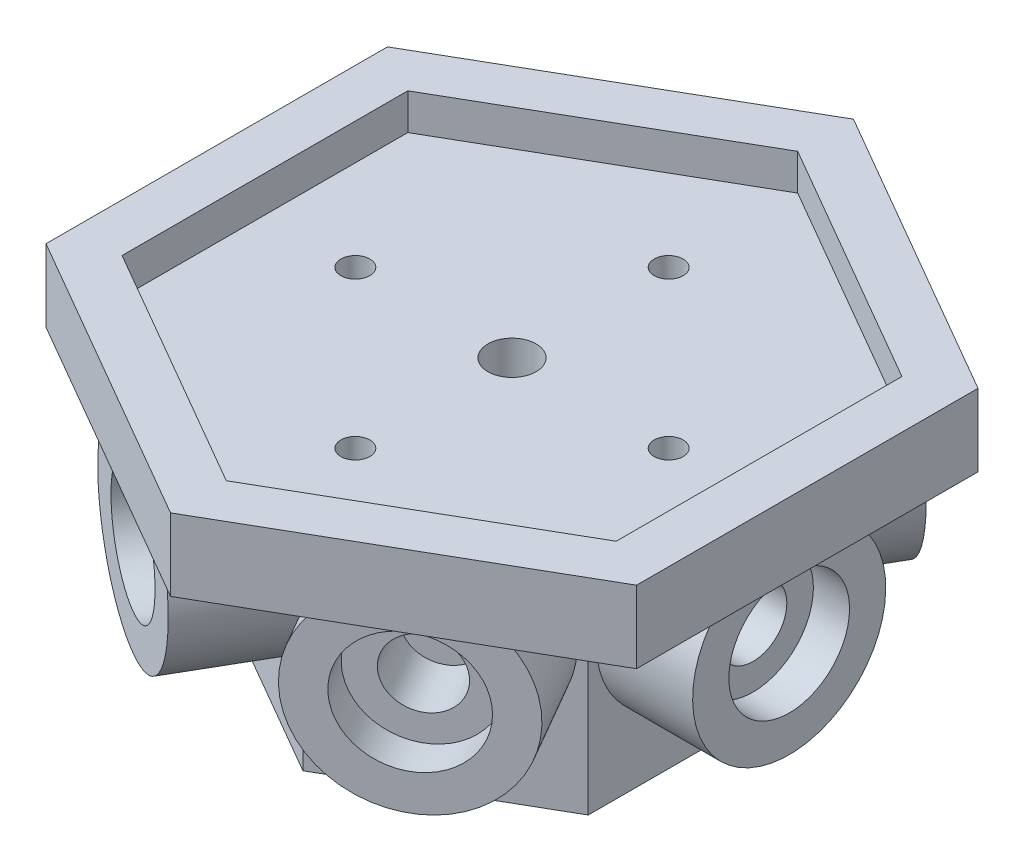
SolidWorks part; units mm, degrees
ref_plane "Front Plane" through (0, 0, 0) normal (0, 0, 1) x (1, 0, 0)
ref_plane "Top Plane" through (0, 0, 0) normal (0, 1, 0) x (1, 0, 0)
ref_plane "Right Plane" through (0, 0, 0) normal (1, 0, 0) x (0, 0, -1)
sketch "Sketch3" plane through (0, 0, 0) normal (0, 1, 0) x (1, 0, 0)
  line L1 (122.4471, -70.817) -> (122.5528, 70.6338)
  line L2 (122.5528, 70.6338) -> (0.1058, 141.4508)
  line L3 (0.1058, 141.4508) -> (-122.4471, 70.817)
  line L4 (-122.4471, 70.817) -> (-122.5528, -70.6338)
  line L5 (-122.5528, -70.6338) -> (-0.1058, -141.4508)
  line L6 (-0.1058, -141.4508) -> (122.4471, -70.817)
  circle A0 centre (0, 0) radius 122.5 construction
  point P1 (122.5, -0.0916)
  dimension "D1" = 245
extrude "Boss-Extrude2" add sketch "Sketch3" along normal blind 30
sketch "Sketch4" plane through (0, 30, 0) normal (0, 1, 0) x (1, 0, 0)
  line L0 (-122.4471, 70.817) -> (-122.5528, -70.6338) construction
  line L1 (102.4557, -59.255) -> (102.5442, 59.1018)
  line L2 (102.5442, 59.1018) -> (0.0885, 118.3568)
  line L3 (0.0885, 118.3568) -> (-102.4557, 59.255)
  line L4 (-102.4557, 59.255) -> (-102.5442, -59.1018)
  line L5 (-102.5442, -59.1018) -> (-0.0885, -118.3568)
  line L6 (-0.0885, -118.3568) -> (102.4557, -59.255)
  circle A0 centre (0, 0) radius 102.5 construction
  dimension "D1" = 205
extrude "Cut-Extrude1" cut sketch "Sketch4" against normal blind 15 contours L3 L4 L5 L6 L1 L2
sketch "Sketch5" plane through (0, 0, 0) normal (0, -1, 0) x (1, 0, 0)
  line L0 (-122.4471, -70.817) -> (-122.5528, 70.6338) construction
  line L1 (75.0324, -43.2452) -> (74.9676, 43.3573)
  line L2 (74.9676, 43.3573) -> (-0.0647, 86.6025)
  line L3 (-0.0647, 86.6025) -> (-75.0324, 43.2452)
  line L4 (-75.0324, 43.2452) -> (-74.9676, -43.3573)
  line L5 (-74.9676, -43.3573) -> (0.0647, -86.6025)
  line L6 (0.0647, -86.6025) -> (75.0324, -43.2452)
  circle A0 centre (0, 0) radius 75 construction
  dimension "D1" = 150
extrude "Boss-Extrude4" add sketch "Sketch5" along normal blind 90
sketch "Sketch7" plane through (0, -90, 0) normal (0, -1, 0) x (1, 0, 0)
  circle A0 centre (0, 0) radius 10
  dimension "D1" = 20
extrude "Cut-Extrude2" cut sketch "Sketch7" against normal blind 120
sketch "Sketch8" plane through (0, -90, 0) normal (0, -1, 0) x (1, 0, 0)
  circle A0 centre (0, 0) radius 25
  dimension "D1" = 50
extrude "Cut-Extrude3" cut sketch "Sketch8" against normal blind 45
sketch "Sketch9" plane through (0, -90, 0) normal (0, -1, 0) x (1, 0, 0)
  circle A0 centre (0, 0) radius 40
  dimension "D1" = 80
extrude "Cut-Extrude4" cut sketch "Sketch9" against normal blind 20
sketch "Sketch10" plane through (0, -90, 0) normal (0, -1, 0) x (1, 0, 0)
  line L0 (0, 0) -> (0, 64.95) construction
  circle A0 centre (0, 64.95) radius 6
  circle A1 centre (64.95, 0) radius 6
  circle A2 centre (0, -64.95) radius 6
  circle A3 centre (-64.95, 0) radius 6
  point P14 (0, 0)
  dimension "D2" = 12
  dimension "D1" = 64.95
  dimension "D3" = 4
extrude "Cut-Extrude5" cut sketch "Sketch10" against normal blind 120 contours A3 | A0 | A1 | A2
sketch "Sketch12" plane through (75, 0, 0.0561) normal (1, 0, 0.0007) x (0.0007, 0, -1)
  line L0 (0, 30) -> (0, -30) construction
  line L1 (-70.7254, 30) -> (70.7254, 30) construction
  line L2 (-26.4575, 0) -> (26.4575, 0)
  line L3 (43.3013, 0) -> (-43.3013, 0) construction
  arc A0 (-26.4575, 0) -> (26.4575, 0) centre (0, -30) ccw
  dimension "D2" = 80
  dimension "D1" = 60
extrude "Boss-Extrude8" add sketch "Sketch12" along normal blind 40 contours L2 A0
sketch "Sketch15" plane through (115, 0, 0.086) normal (1, 0, 0.0007) x (0.0007, 0, -1)
  circle A1 centre (0, -30) radius 14
  dimension "D1" = 28
extrude "Cut-Extrude7" cut sketch "Sketch15" against normal blind 40 contours A1
sketch "Sketch17" plane through (115, 0, 0.086) normal (1, 0, 0.0007) x (0.0007, 0, -1)
  circle A0 centre (0, -30) radius 25
  dimension "D1" = 50
extrude "Cut-Extrude8" cut sketch "Sketch17" against normal blind 15
pattern_circular "CirPattern1" count 6 over 360 about axis through (0, 0, 0) along (0, 1, 0) of "Boss-Extrude8", "Cut-Extrude8", "Cut-Extrude7"
